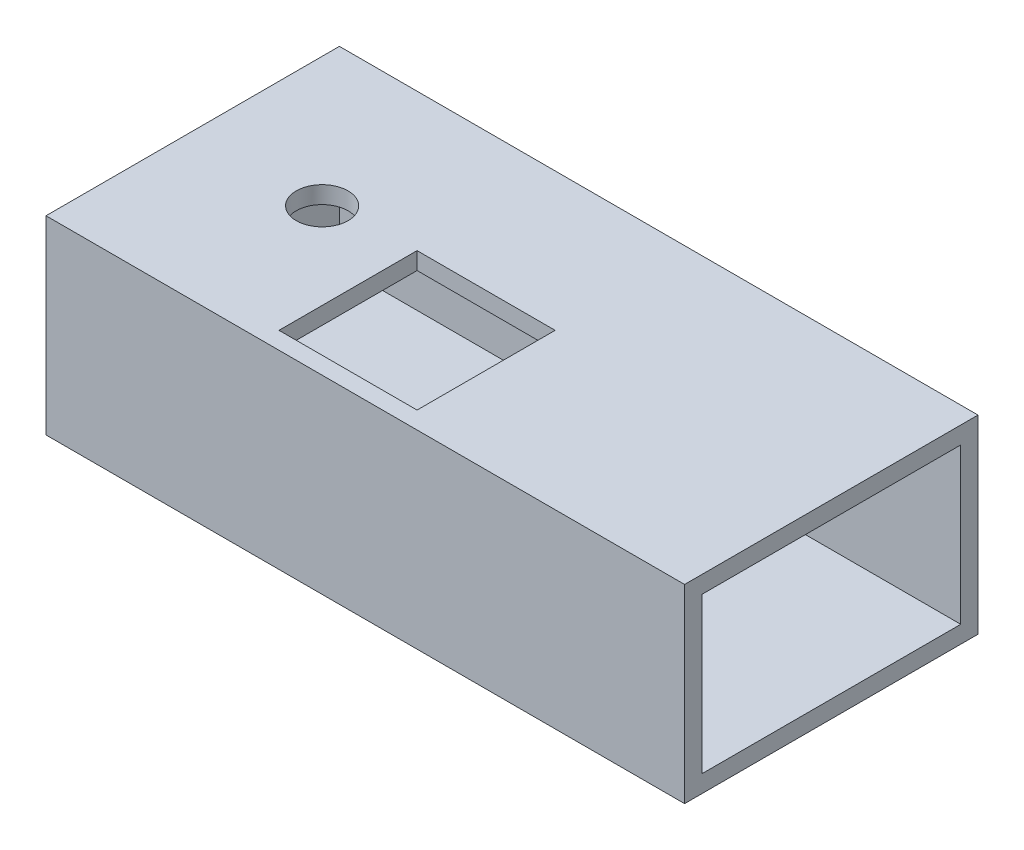
SolidWorks part; units mm, degrees
ref_plane "Front Plane" through (0, 0, 0) normal (0, 0, 1) x (1, 0, 0)
ref_plane "Top Plane" through (0, 0, 0) normal (0, 1, 0) x (1, 0, 0)
ref_plane "Right Plane" through (0, 0, 0) normal (1, 0, 0) x (0, 0, -1)
sketch "Sketch1" plane through (0, 0, 0) normal (0, 1, 0) x (1, 0, 0)
  line L0 (0, 8.5) -> (0, -8.5) construction
  line L5 (-18.5, 8.5) -> (18.5, 8.5)
  line L6 (18.5, -8.5) -> (18.5, 8.5)
  line L7 (-18.5, -8.5) -> (18.5, -8.5)
  line L8 (-18.5, -8.5) -> (-18.5, 8.5)
  point P0 (0, 8.5)
  point P6 (0, 0)
  dimension "D1" = 17
  dimension "D2" = 37
extrude "Boss-Extrude1" add sketch "Sketch1" along normal blind 11
shell "Shell1" thickness 1
sketch "Sketch2" plane through (-18.5, 0, 0) normal (-1, 0, 0) x (0, 0, 1)
  line L0 (0, 11) -> (0, 0) construction
  line L1 (-8.5, 11) -> (8.5, 11) construction
  line L3 (-5, 6) -> (5, 6)
  line L4 (-5, 6) -> (-5, 9.5)
  line L5 (-5, 9.5) -> (5, 9.5)
  line L6 (5, 6) -> (5, 9.5)
  line L7 (-5, 6) -> (5, 9.5) construction
  line L8 (-5, 9.5) -> (5, 6) construction
  point P5 (0, 7.75)
  dimension "D1" = 1.5
  dimension "D2" = 3.5
  dimension "D3" = 10
extrude "Cut-Extrude1" cut sketch "Sketch2" against normal blind 11
sketch "Sketch3" plane through (0, 11, 0) normal (0, 1, 0) x (1, 0, 0)
  line L0 (-17.5, -7.5) -> (2, -7.5) construction
  line L1 (-17.5, -7.5) -> (18.5, -7.5) construction
  line L2 (-17.5, 0) -> (-11, 0) construction
  line L3 (2, -7.5) -> (-6, -7.5)
  line L4 (2, -7.5) -> (2, 0.5)
  line L5 (2, 0.5) -> (-6, 0.5)
  line L6 (-6, -7.5) -> (-6, 0.5)
  line L7 (-17.5, 7.5) -> (-17.5, -7.5) construction
  circle A0 centre (-11, 0) radius 1.5
  dimension "D1" = 8
  dimension "D2" = 8
  dimension "D3" = 6.5
extrude "Cut-Extrude2" cut sketch "Sketch3" against normal blind 2
